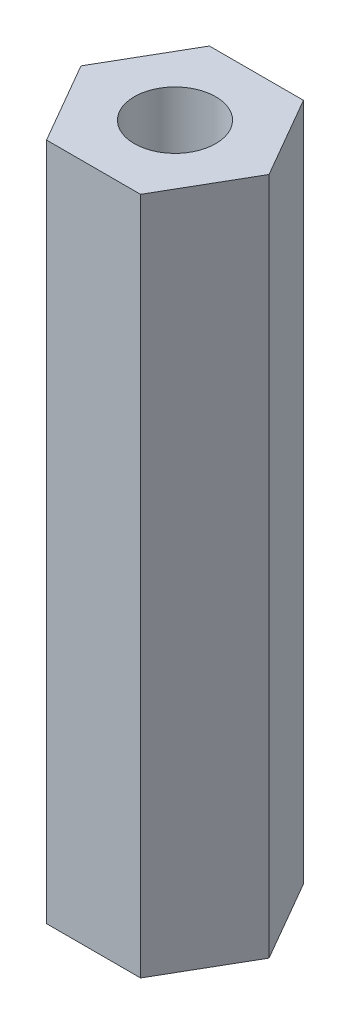
SolidWorks part; units mm, degrees
ref_plane "Front Plane" through (0, 0, 0) normal (0, 0, 1) x (1, 0, 0)
ref_plane "Top Plane" through (0, 0, 0) normal (0, 1, 0) x (1, 0, 0)
ref_plane "Right Plane" through (0, 0, 0) normal (1, 0, 0) x (0, 0, -1)
sketch "Sketch1" plane through (0, 0, 0) normal (0, 1, 0) x (1, 0, 0)
  line L0 (-1.7321, 3) -> (-3.4641, 0)
  line L1 (-3.4641, 0) -> (-1.7321, -3)
  line L2 (-1.7321, -3) -> (1.7321, -3)
  line L3 (1.7321, -3) -> (3.4641, 0)
  line L4 (3.4641, 0) -> (1.7321, 3)
  line L5 (1.7321, 3) -> (-1.7321, 3)
  line L6 (1.7321, 3) -> (1.7321, -3) construction
  line L7 (3.4641, 0) -> (-1.7321, 3) construction
  line L8 (-3.4641, 0) -> (1.7321, 3) construction
  line L9 (1.7321, -3) -> (-1.7321, 3) construction
  circle A1 centre (0, 0) radius 1.5
  point P0 (0, 0)
  dimension "D2" = 3
  dimension "D1" = 6
extrude "Boss-Extrude1" add sketch "Sketch1" along normal blind 25
